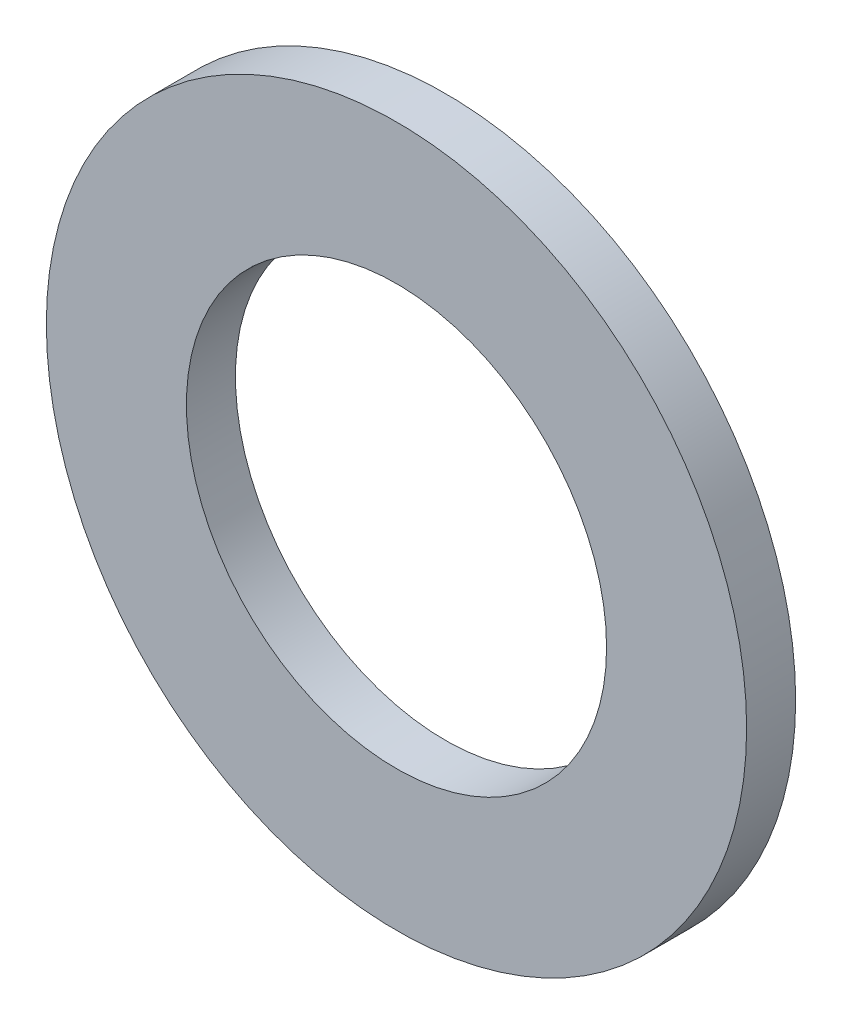
SolidWorks part; units mm, degrees
material "7075-T6 (SN)"
ref_plane "Front Plane" through (0, 0, 0) normal (0, 0, 1) x (1, 0, 0)
ref_plane "Top Plane" through (0, 0, 0) normal (0, 1, 0) x (1, 0, 0)
ref_plane "Right Plane" through (0, 0, 0) normal (1, 0, 0) x (0, 0, -1)
sketch "Sketch1" plane through (0, 0, 0) normal (0, 0, 1) x (1, 0, 0)
  circle A0 centre (0, 0) radius 6
  circle A1 centre (0, 0) radius 10
  dimension "D1" = 12
  dimension "D2" = 20
extrude "Boss-Extrude1" add sketch "Sketch1" along normal blind 1.4
